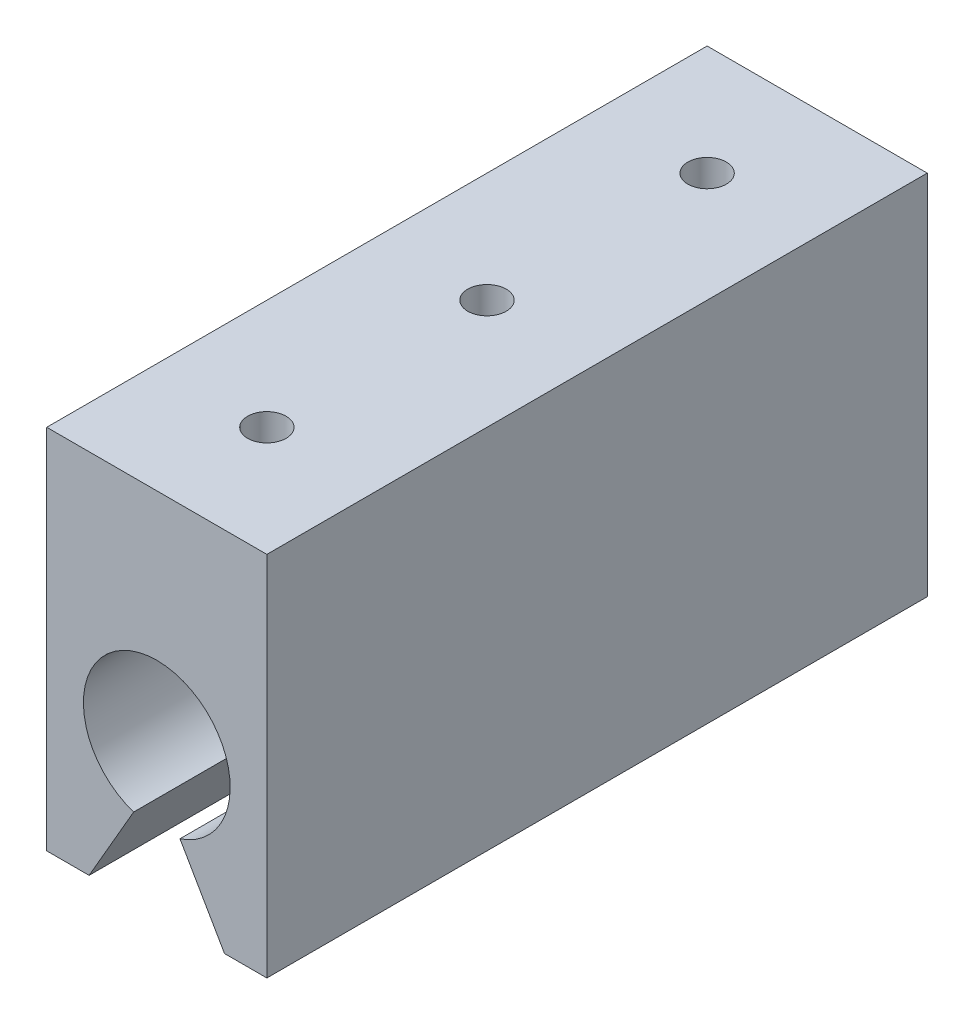
SolidWorks part; units mm, degrees
ref_plane "Front Plane" through (0, 0, 0) normal (0, 0, 1) x (1, 0, 0)
ref_plane "Top Plane" through (0, 0, 0) normal (0, 1, 0) x (1, 0, 0)
ref_plane "Right Plane" through (0, 0, 0) normal (1, 0, 0) x (0, 0, -1)
sketch "Sketch1" plane through (0, 0, 0) normal (0, 0, 1) x (1, 0, 0)
  line L0 (19.05, 0) -> (-19.05, 0) construction
  line L1 (0, 0) -> (0, 38.1) construction
  line L2 (-19.05, 0) -> (-4.0102, 26.0497) construction
  line L3 (4.0102, 26.0497) -> (19.05, 0) construction
  line L4 (4.0102, 26.0497) -> (11.7177, 12.7)
  line L5 (11.7177, 12.7) -> (19.05, 12.7)
  line L6 (19.05, 12.7) -> (19.05, 76.2)
  line L7 (19.05, 76.2) -> (-19.05, 76.2)
  line L8 (-19.05, 76.2) -> (-19.05, 12.7)
  line L9 (-19.05, 12.7) -> (-11.7177, 12.7)
  line L10 (-11.7177, 12.7) -> (-4.0102, 26.0497)
  line L11 (-19.05, 0) -> (-30.0508, 0) construction
  line L12 (-30.0508, 0) -> (-30.0508, 76.2) construction
  line L13 (-30.0508, 76.2) -> (-19.05, 76.2) construction
  arc A0 (4.0102, 26.0497) -> (-4.0102, 26.0497) centre (0, 38.1) ccw
  point P4 (0, 0)
  point P9 (-30.0508, 38.1)
  dimension "D2" = 25.4
  dimension "D1" = 38.1
  dimension "D3" = 60
  dimension "D5" = 76.2
  dimension "D6" = 38.1
  dimension "D7" = 63.5
extrude "Boss-Extrude1" add sketch "Sketch1" along normal blind 114.3
sketch "Sketch2" plane through (0, 76.2, 0) normal (0, 1, 0) x (1, 0, 0)
  line L0 (0, 0) -> (0, -114.3) construction
  line L1 (19.05, 0) -> (-19.05, 0) construction
  line L2 (19.05, -114.3) -> (-19.05, -114.3) construction
  circle A0 centre (0, -19.05) radius 3.3274
  circle A1 centre (0, -57.15) radius 3.3274
  circle A2 centre (0, -95.25) radius 3.3274
  dimension "D1" = 6.6548
  dimension "D2" = 19.05
  dimension "D3" = 38.1
  dimension "D4" = 38.1
extrude "Cut-Extrude1" cut sketch "Sketch2" against normal through all
ref_plane "Plane1" through (0, 63.5, 0) normal (0, 1, 0) x (1, 0, 0)
sketch "Sketch3" plane through (0, 63.5, 0) normal (0, 1, 0) x (1, 0, 0)
  circle A0 centre (0, -19.05) radius 6.35
  circle A1 centre (0, -57.15) radius 6.35
  circle A2 centre (0, -95.25) radius 6.35
  dimension "D1" = 12.7
extrude "Cut-Extrude2" cut sketch "Sketch3" against normal up to next
